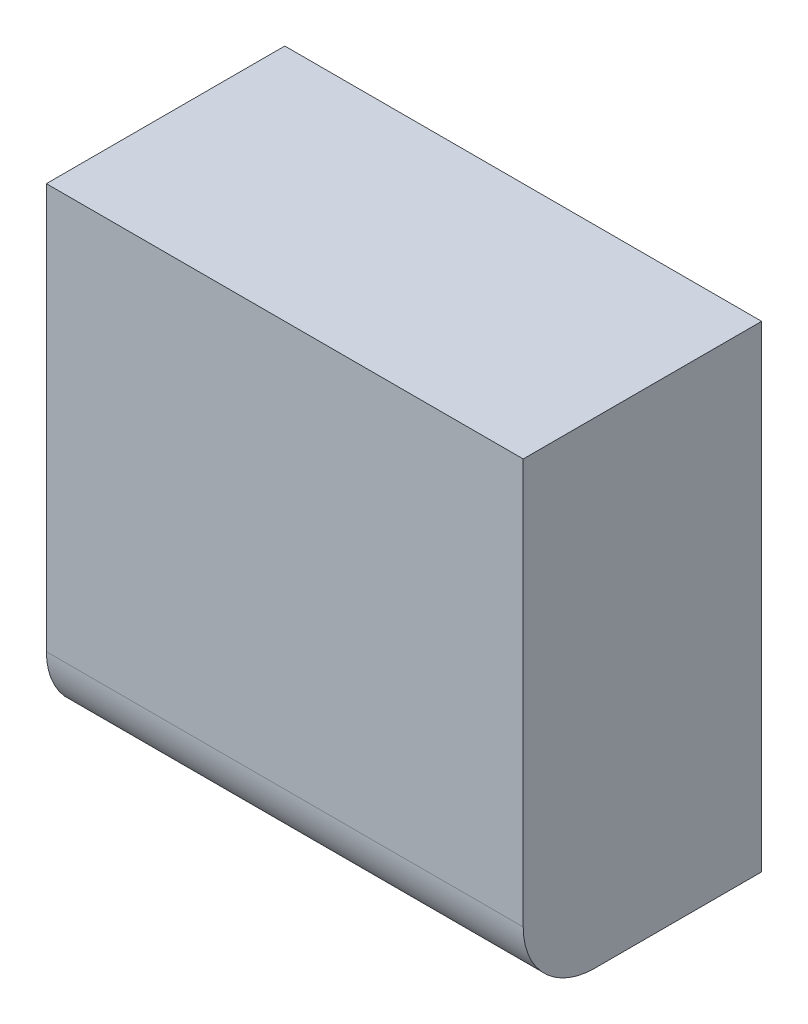
SolidWorks part; units mm, degrees
ref_plane "Front Plane" through (0, 0, 0) normal (0, 0, 1) x (1, 0, 0)
ref_plane "Top Plane" through (0, 0, 0) normal (0, 1, 0) x (1, 0, 0)
ref_plane "Right Plane" through (0, 0, 0) normal (1, 0, 0) x (0, 0, -1)
sketch "Sketch1" plane through (0, 0, 0) normal (0, 0, 1) x (1, 0, 0)
  line L1 (0, 0) -> (20, 0)
  line L2 (0, 0) -> (0, 20)
  line L3 (0, 20) -> (20, 20)
  line L4 (20, 0) -> (20, 20)
extrude "Boss-Extrude1" add sketch "Sketch1" along normal blind 10
fillet "Fillet1" radius 3 1 edges at (10, 0, 10)
